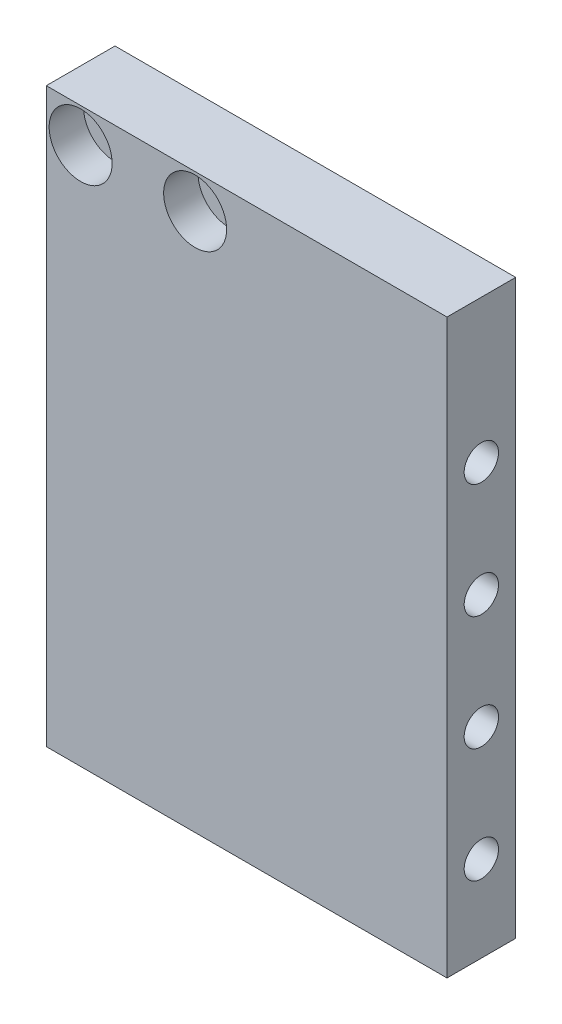
SolidWorks part; units mm, degrees
ref_plane "前视基准面" through (0, 0, 0) normal (0, 0, 1) x (1, 0, 0)
ref_plane "上视基准面" through (0, 0, 0) normal (0, 1, 0) x (1, 0, 0)
ref_plane "右视基准面" through (0, 0, 0) normal (1, 0, 0) x (0, 0, -1)
sketch "草图1" plane through (0, 0, 0) normal (0, 0, 1) x (1, 0, 0)
  line L1 (35, -50) -> (-35, -50)
  line L2 (35, -50) -> (35, 50)
  line L3 (35, 50) -> (-35, 50)
  line L4 (-35, -50) -> (-35, 50)
  line L5 (35, -50) -> (-35, 50) construction
  line L6 (35, 50) -> (-35, -50) construction
  point P0 (0, 0)
  dimension "D1" = 70
  dimension "D2" = 100
extrude "凸台-拉伸1" add sketch "草图1" along normal blind 12
sketch "草图2" plane through (-35, 0, 0) normal (-1, 0, 0) x (0, 0, 1)
  line L0 (12, -50) -> (0, -50) construction
  line L1 (12, 50) -> (12, -50) construction
  circle A0 centre (6, -35) radius 3
  circle A1 centre (6, -15) radius 3
  circle A2 centre (6, 5) radius 3
  circle A3 centre (6, 25) radius 3
  dimension "D1" = 6
  dimension "D2" = 6
  dimension "D3" = 6
  dimension "D4" = 6
  dimension "D5" = 20
  dimension "D6" = 20
  dimension "D7" = 20
  dimension "D8" = 15
extrude "切除-拉伸1" cut sketch "草图2" against normal blind 10
sketch "草图3" plane through (0, 0, 12) normal (0, 0, 1) x (1, 0, 0)
  line L0 (35, 50) -> (-35, 50) construction
  line L2 (-35, 50) -> (-35, -50) construction
  circle A0 centre (-29, 44) radius 3
  circle A1 centre (-9, 44) radius 3
  dimension "D1" = 6
  dimension "D5" = 6
  dimension "D6" = 6
  dimension "D2" = 6
  dimension "D3" = 20
  dimension "D4" = 6
extrude "切除-拉伸2" cut sketch "草图3" against normal blind 12
sketch "草图4" plane through (0, 0, 12) normal (0, 0, 1) x (1, 0, 0)
  circle A2 centre (-29, 44) radius 5.5
  circle A3 centre (-29, 44) radius 5.5
  circle A5 centre (-9, 44) radius 5.5
  circle A6 centre (-9, 44) radius 5.5
  dimension "D1" = 2.5
  dimension "D2" = 2.5
extrude "切除-拉伸3" cut sketch "草图4" against normal blind 6
sketch "草图5" plane through (35, 0, 0) normal (1, 0, 0) x (0, 0, -1)
  line L0 (-12, -50) -> (0, -50) construction
  line L2 (-12, -50) -> (-12, 50) construction
  line L3 (-6, -35) -> (-6, -15) construction
  circle A0 centre (-6, -35) radius 3
  circle A1 centre (-6, -15) radius 3
  circle A2 centre (-6, 5) radius 3
  circle A3 centre (-6, 25) radius 3
  dimension "D1" = 6
  dimension "D2" = 15
  dimension "D3" = 6
  dimension "D5" = 20
  dimension "D4" = 4
extrude "切除-拉伸4" cut sketch "草图5" against normal blind 10
sketch "草图6" plane through (0, -50, 0) normal (0, -1, 0) x (1, 0, 0)
  line L0 (-35, 12) -> (-35, 0) construction
  line L1 (-35, 12) -> (35, 12) construction
  circle A0 centre (-21, 6) radius 3
  circle A1 centre (-7, 6) radius 3
  circle A2 centre (7, 6) radius 3
  circle A3 centre (21, 6) radius 3
  dimension "D1" = 6
  dimension "D2" = 14
  dimension "D3" = 6
  dimension "D4" = 4
extrude "切除-拉伸5" cut sketch "草图6" against normal blind 10
